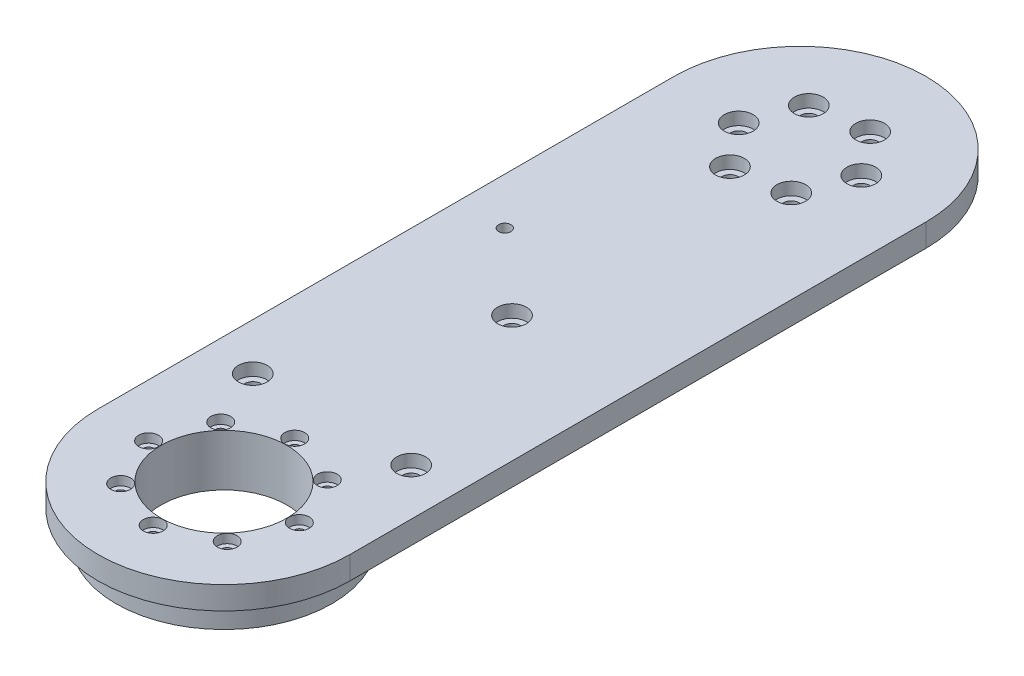
SolidWorks part; units mm, degrees
material "Aleación 6061"
ref_plane "Alzado" through (0, 0, 0) normal (0, 0, 1) x (1, 0, 0)
ref_plane "Planta" through (0, 0, 0) normal (0, 1, 0) x (1, 0, 0)
ref_plane "Vista lateral" through (0, 0, 0) normal (1, 0, 0) x (0, 0, -1)
sketch "Sk_Placa" plane through (0, 0, 0) normal (0, 1, 0) x (1, 0, 0)
  line L1 (-35, -330) -> (35, -330)
  line L2 (-35, -330) -> (-35, -170)
  line L3 (-35, -170) -> (35, -170)
  line L4 (35, -330) -> (35, -170)
  line L5 (-35, -330) -> (35, -170) construction
  line L6 (-35, -170) -> (35, -330) construction
  point P0 (0, -250)
  dimension "D1" = 70
  dimension "D2" = 160
  dimension "D3" = 250
extrude "Placa" add sketch "Sk_Placa" along normal blind 6.35 from offset 46.75
sketch "Sk_Extremos" plane through (0, 0, 0) normal (0, 1, 0) x (1, 0, 0)
  circle A0 centre (0, -170) radius 35
  circle A1 centre (0, -330) radius 35
  dimension "D1" = 70
  dimension "D3" = 70
  dimension "D2" = 170
  dimension "D4" = 330
extrude "Extremos" add sketch "Sk_Extremos" along normal blind 6.35 from offset 46.75
sketch "Sk_Pasantes_M4_separadores" plane through (0, 0, 0) normal (0, 1, 0) x (1, 0, 0)
  circle A0 centre (0, -250) radius 2.25
  circle A1 centre (-22, -300) radius 2.25
  circle A2 centre (22, -300) radius 2.25
  dimension "D1" = 4.5
  dimension "D3" = 4.5
  dimension "D6" = 4.5
  dimension "D2" = 250
  dimension "D4" = 22
  dimension "D5" = 300
  dimension "D7" = 22
  dimension "D8" = 300
extrude "Pasantes_M4_separadores" cut sketch "Sk_Pasantes_M4_separadores" along normal blind 6.35 from offset 46.75
sketch "Sk_Asiento_J3" plane through (0, 0, 0) normal (0, 1, 0) x (1, 0, 0)
  circle A0 centre (0, -330) radius 30
  circle A1 centre (0, -330) radius 17.5
  dimension "D1" = 60
  dimension "D3" = 35
  dimension "D2" = 330
  dimension "D4" = 330
extrude "Asiento_J3" add sketch "Sk_Asiento_J3" along normal blind 8 from offset 38.75
sketch "Sk_Paso_rotor_J3" plane through (0, 0, 0) normal (0, 1, 0) x (1, 0, 0)
  circle A0 centre (0, -330) radius 17.5
  dimension "D1" = 35
  dimension "D2" = 330
extrude "Paso_rotor_J3" cut sketch "Sk_Paso_rotor_J3" along normal blind 14.35 from offset 38.75
sketch "Sk_Pasantes_M2-5_estator_J3" plane through (0, 0, 0) normal (0, 1, 0) x (1, 0, 0)
  circle A0 centre (20.29, -329.3624) radius 1.45
  circle A1 centre (14.7981, -343.8963) radius 1.45
  circle A2 centre (0.6376, -350.29) radius 1.45
  circle A3 centre (-13.8963, -344.7981) radius 1.45
  circle A4 centre (-20.29, -330.6376) radius 1.45
  circle A5 centre (-14.7981, -316.1037) radius 1.45
  circle A6 centre (-0.6376, -309.71) radius 1.45
  circle A7 centre (13.8963, -315.2019) radius 1.45
  dimension "D1" = 2.9
  dimension "D4" = 2.9
  dimension "D7" = 2.9
  dimension "D10" = 2.9
  dimension "D13" = 2.9
  dimension "D16" = 2.9
  dimension "D19" = 2.9
  dimension "D22" = 2.9
  dimension "D2" = 20.29
  dimension "D3" = 329.3624
  dimension "D5" = 14.7981
  dimension "D6" = 343.8963
  dimension "D8" = 0.6376
  dimension "D9" = 350.29
  dimension "D11" = 13.8963
  dimension "D12" = 344.7981
  dimension "D14" = 20.29
  dimension "D15" = 330.6376
  dimension "D17" = 14.7981
  dimension "D18" = 316.1037
  dimension "D20" = 0.6376
  dimension "D21" = 309.71
  dimension "D23" = 13.8963
  dimension "D24" = 315.2019
extrude "Pasantes_M2-5_estator_J3" cut sketch "Sk_Pasantes_M2-5_estator_J3" along normal blind 14.35 from offset 38.75
sketch "Sk_Cajas_M2-5_J3" plane through (0, 0, 0) normal (0, 1, 0) x (1, 0, 0)
  circle A0 centre (20.29, -329.3624) radius 2.75
  circle A1 centre (14.7981, -343.8963) radius 2.75
  circle A2 centre (0.6376, -350.29) radius 2.75
  circle A3 centre (-13.8963, -344.7981) radius 2.75
  circle A4 centre (-20.29, -330.6376) radius 2.75
  circle A5 centre (-14.7981, -316.1037) radius 2.75
  circle A6 centre (-0.6376, -309.71) radius 2.75
  circle A7 centre (13.8963, -315.2019) radius 2.75
  dimension "D1" = 5.5
  dimension "D4" = 5.5
  dimension "D7" = 5.5
  dimension "D10" = 5.5
  dimension "D13" = 5.5
  dimension "D16" = 5.5
  dimension "D19" = 5.5
  dimension "D22" = 5.5
  dimension "D2" = 20.29
  dimension "D3" = 329.3624
  dimension "D5" = 14.7981
  dimension "D6" = 343.8963
  dimension "D8" = 0.6376
  dimension "D9" = 350.29
  dimension "D11" = 13.8963
  dimension "D12" = 344.7981
  dimension "D14" = 20.29
  dimension "D15" = 330.6376
  dimension "D17" = 14.7981
  dimension "D18" = 316.1037
  dimension "D20" = 0.6376
  dimension "D21" = 309.71
  dimension "D23" = 13.8963
  dimension "D24" = 315.2019
extrude "Cajas_M2-5_J3" cut sketch "Sk_Cajas_M2-5_J3" along normal blind 2.5 from offset 50.6
sketch "Sk_Pasantes_M4_salida_J2" plane through (0, 0, 0) normal (0, 1, 0) x (1, 0, 0)
  circle A0 centre (14.8391, -167.8088) radius 2.25
  circle A1 centre (9.3172, -181.7554) radius 2.25
  circle A2 centre (-5.5219, -183.9466) radius 2.25
  circle A3 centre (-14.8391, -172.1912) radius 2.25
  circle A4 centre (-9.3172, -158.2446) radius 2.25
  circle A5 centre (5.5219, -156.0534) radius 2.25
  dimension "D1" = 4.5
  dimension "D4" = 4.5
  dimension "D7" = 4.5
  dimension "D10" = 4.5
  dimension "D13" = 4.5
  dimension "D16" = 4.5
  dimension "D2" = 14.8391
  dimension "D3" = 167.8088
  dimension "D5" = 9.3172
  dimension "D6" = 181.7554
  dimension "D8" = 5.5219
  dimension "D9" = 183.9466
  dimension "D11" = 14.8391
  dimension "D12" = 172.1912
  dimension "D14" = 9.3172
  dimension "D15" = 158.2446
  dimension "D17" = 5.5219
  dimension "D18" = 156.0534
extrude "Pasantes_M4_salida_J2" cut sketch "Sk_Pasantes_M4_salida_J2" along normal blind 6.35 from offset 46.75
sketch "Sk_Cajas_M4_J2" plane through (0, 0, 0) normal (0, 1, 0) x (1, 0, 0)
  circle A0 centre (14.8391, -167.8088) radius 4
  circle A1 centre (9.3172, -181.7554) radius 4
  circle A2 centre (-5.5219, -183.9466) radius 4
  circle A3 centre (-14.8391, -172.1912) radius 4
  circle A4 centre (-9.3172, -158.2446) radius 4
  circle A5 centre (5.5219, -156.0534) radius 4
  dimension "D1" = 8
  dimension "D4" = 8
  dimension "D7" = 8
  dimension "D10" = 8
  dimension "D13" = 8
  dimension "D16" = 8
  dimension "D2" = 14.8391
  dimension "D3" = 167.8088
  dimension "D5" = 9.3172
  dimension "D6" = 181.7554
  dimension "D8" = 5.5219
  dimension "D9" = 183.9466
  dimension "D11" = 14.8391
  dimension "D12" = 172.1912
  dimension "D14" = 9.3172
  dimension "D15" = 158.2446
  dimension "D17" = 5.5219
  dimension "D18" = 156.0534
extrude "Cajas_M4_J2" cut sketch "Sk_Cajas_M4_J2" along normal blind 3.5 from offset 49.6
sketch "Sk_Pasante_M3_cincho" plane through (0, 0, 0) normal (0, 1, 0) x (1, 0, 0)
  circle A0 centre (-22, -230) radius 1.7
  dimension "D1" = 3.4
  dimension "D2" = 22
  dimension "D3" = 230
extrude "Pasante_M3_cincho" cut sketch "Sk_Pasante_M3_cincho" along normal blind 6.35 from offset 46.75
sketch "Sk_Cajas_M4_separadores" plane through (0, 53.1, 0) normal (0, 1, 0) x (1, 0, 0)
  circle A0 centre (0, -250) radius 4
  circle A1 centre (22, -300) radius 4
  circle A2 centre (-22, -300) radius 4
extrude "Cajas_M4_separadores" cut sketch "Sk_Cajas_M4_separadores" against normal blind 3.5
